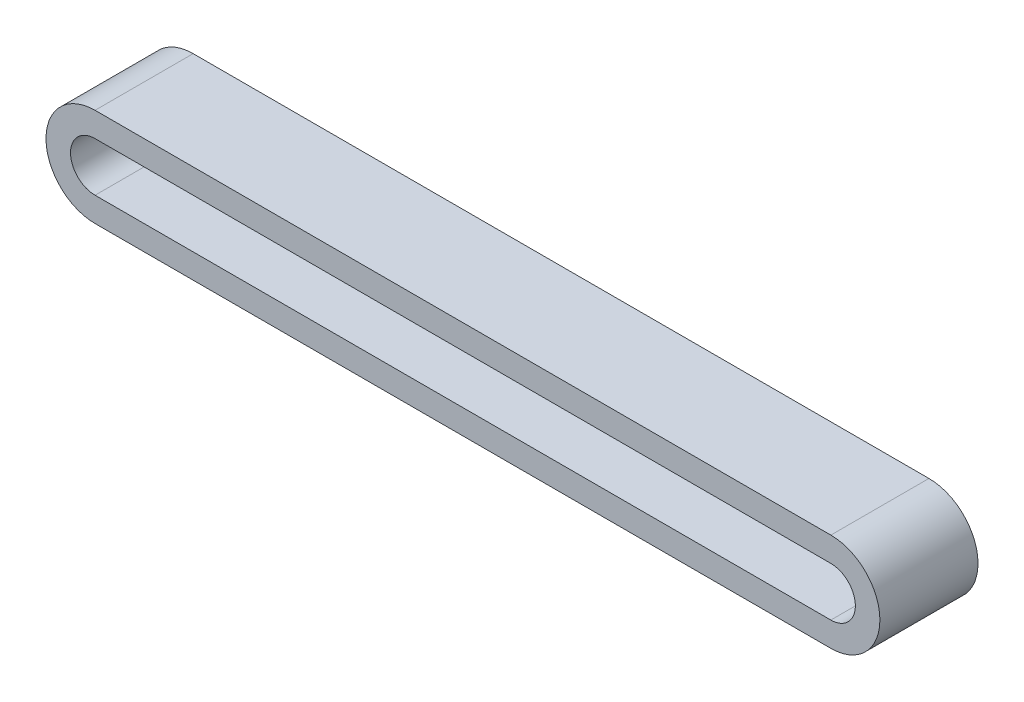
SolidWorks part; units mm, degrees
ref_plane "Alzado" through (0, 0, 0) normal (0, 0, 1) x (1, 0, 0)
ref_plane "Planta" through (0, 0, 0) normal (0, 1, 0) x (1, 0, 0)
ref_plane "Vista lateral" through (0, 0, 0) normal (1, 0, 0) x (0, 0, -1)
sketch "Croquis1" plane through (0, 0, 0) normal (0, 0, 1) x (1, 0, 0)
  line L0 (-75, 0) -> (75, 0) construction
  line L1 (-75, 5) -> (75, 5)
  line L2 (-75, -5) -> (75, -5)
  line L3 (75, 0) -> (-75, 0) construction
  line L4 (75, -10) -> (-75, -10)
  line L5 (75, 10) -> (-75, 10)
  arc A0 (-75, 5) -> (-75, -5) centre (-75, 0) ccw
  arc A1 (75, -5) -> (75, 5) centre (75, 0) ccw
  arc A2 (75, -10) -> (75, 10) centre (75, 0) ccw
  arc A3 (-75, 10) -> (-75, -10) centre (-75, 0) ccw
  point P2 (0, 0)
  point P7 (0, 0)
  point P15 (0, 0)
  dimension "D1" = 5
  dimension "D2" = 10
  dimension "D3" = 150
extrude "Saliente-Extruir1" add sketch "Croquis1" along normal blind 20
